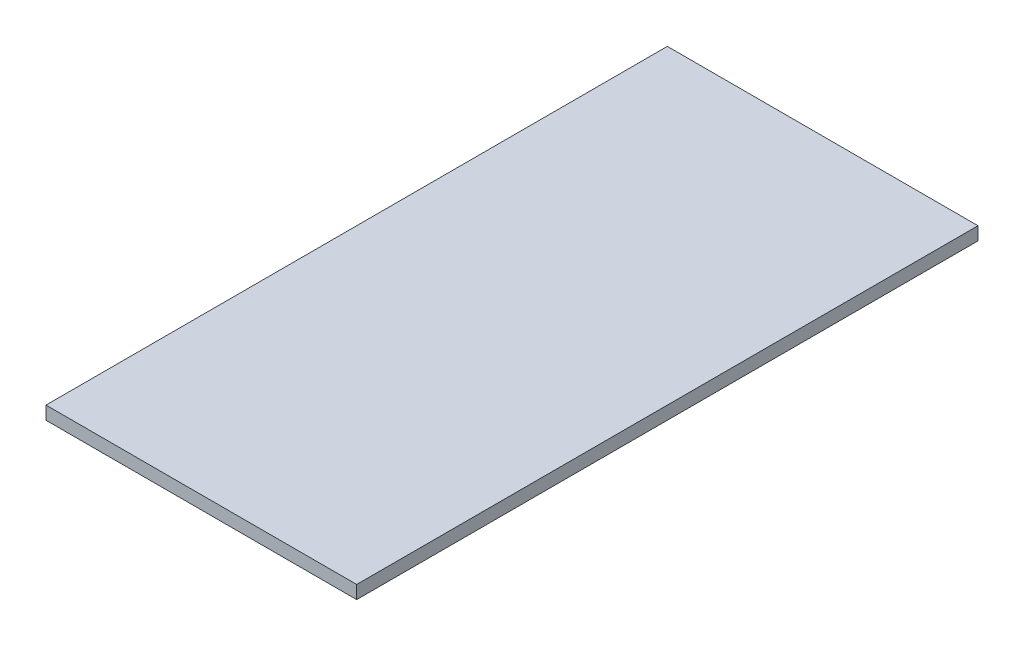
SolidWorks part; units mm, degrees
ref_plane "Front Plane" through (0, 0, 0) normal (0, 0, 1) x (1, 0, 0)
ref_plane "Top Plane" through (0, 0, 0) normal (0, 1, 0) x (1, 0, 0)
ref_plane "Right Plane" through (0, 0, 0) normal (1, 0, 0) x (0, 0, -1)
sketch "Sketch1" plane through (0, 0, 0) normal (0, 1, 0) x (1, 0, 0)
  line L1 (-75, -150) -> (75, -150)
  line L2 (-75, -150) -> (-75, 150)
  line L3 (-75, 150) -> (75, 150)
  line L4 (75, -150) -> (75, 150)
  line L5 (-75, -150) -> (75, 150) construction
  line L6 (-75, 150) -> (75, -150) construction
  point P0 (0, 0)
  dimension "D1" = 300
  dimension "D2" = 150
extrude "Boss-Extrude1" add sketch "Sketch1" along normal blind 6.35
